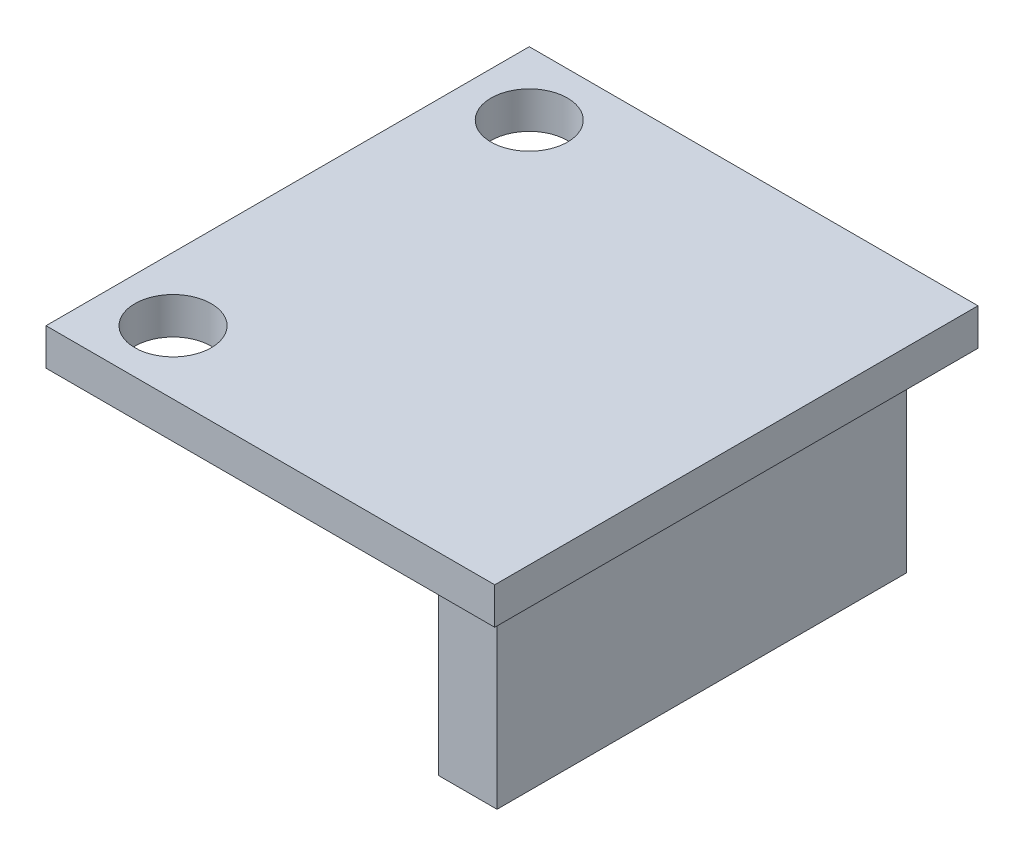
SolidWorks part; units mm, degrees
ref_plane "Front Plane" through (0, 0, 0) normal (0, 0, 1) x (1, 0, 0)
ref_plane "Top Plane" through (0, 0, 0) normal (0, 1, 0) x (1, 0, 0)
ref_plane "Right Plane" through (0, 0, 0) normal (1, 0, 0) x (0, 0, -1)
sketch "Sketch1" plane through (0, 0, 0) normal (0, 1, 0) x (1, 0, 0)
  line L0 (-25.5726, -14.8066) -> (-25.5726, -15.9066) construction
  line L1 (-28.3333, -15.9066) -> (-8.8333, -15.9066)
  line L2 (-28.3333, -15.9066) -> (-28.3333, 5.0934)
  line L3 (-28.3333, 5.0934) -> (-8.8333, 5.0934)
  line L4 (-8.8333, -15.9066) -> (-8.8333, 5.0934)
  line L5 (-27.2333, -13.1459) -> (-28.3333, -13.1459) construction
  line L6 (-28.3333, -5.4066) -> (-8.8333, -5.4066) construction
  circle A0 centre (-25.5726, -13.1459) radius 1.6607
  circle A1 centre (-25.5726, 2.3327) radius 1.6607
  dimension "D3" = 1.1
  dimension "D1" = 21
  dimension "D2" = 19.5
  dimension "D4" = 1.1
extrude "Extrude1" add sketch "Sketch1" along normal blind 1.6
sketch "Sketch2" plane through (0, 0, 0) normal (0, -1, 0) x (1, 0, 0)
  line L0 (-8.8333, 15.9066) -> (-8.8333, -5.0934) construction
  line L1 (-10.3333, 14.3066) -> (-12.8733, 14.3066)
  line L2 (-10.3333, 14.3066) -> (-10.3333, -3.4934)
  line L3 (-10.3333, -3.4934) -> (-12.8733, -3.4934)
  line L4 (-12.8733, 14.3066) -> (-12.8733, -3.4934)
  line L5 (-10.3333, 14.3066) -> (-10.3333, 15.9066) construction
  line L6 (-28.3333, 15.9066) -> (-8.8333, 15.9066) construction
  line L7 (-10.3333, -3.4934) -> (-10.3333, -5.0934) construction
  line L8 (-8.8333, -5.0934) -> (-28.3333, -5.0934) construction
  dimension "D1" = 2.54
  dimension "D2" = 17.8
  dimension "D3" = 1.5
extrude "Extrude2" add sketch "Sketch2" along normal blind 8.4
